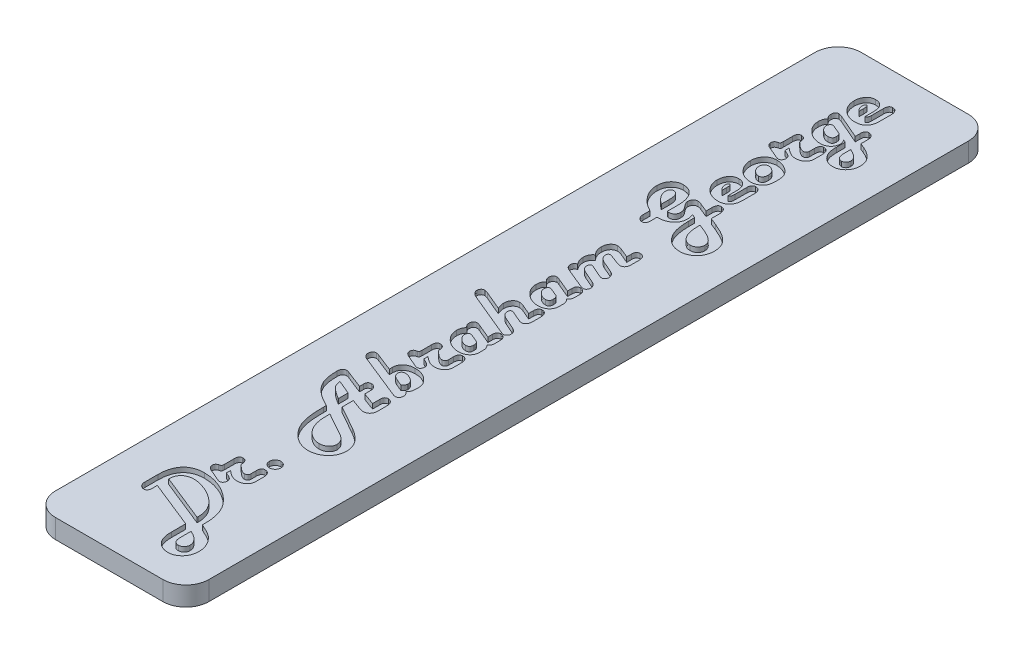
SolidWorks part; units mm, degrees
ref_plane "Front Plane" through (0, 0, 0) normal (0, 0, 1) x (1, 0, 0)
ref_plane "Top Plane" through (0, 0, 0) normal (0, 1, 0) x (1, 0, 0)
ref_plane "Right Plane" through (0, 0, 0) normal (1, 0, 0) x (0, 0, -1)
sketch "Sketch1" plane through (0, 0, 0) normal (0, 0, 1) x (1, 0, 0)
  line L0 (0, 1.5875) -> (0, -1.5875)
  line L1 (-12.7, 0) -> (12.7, 0) construction
  point P6 (0, 0)
  dimension "Width" = 25.4
  dimension "Thk" = 3.175
sketch "Sketch2" plane through (0, 0, 0) normal (1, 0, 0) x (0, 0, -1)
  line L0 (66.675, 0) -> (-66.675, 0)
  point P4 (0, 0)
  dimension "Length" = 133.35
sketch "Sketch3" plane through (0, 0, 0) normal (0, 0, 1) x (1, 0, 0)
  line L1 (12.7, 1.5875) -> (-12.7, 1.5875)
  line L2 (12.7, 1.5875) -> (12.7, -1.5875)
  line L3 (12.7, -1.5875) -> (-12.7, -1.5875)
  line L4 (-12.7, 1.5875) -> (-12.7, -1.5875)
  line L5 (12.7, 1.5875) -> (-12.7, -1.5875) construction
  line L6 (12.7, -1.5875) -> (-12.7, 1.5875) construction
  point P0 (0, 0)
extrude "Boss-Extrude1" add sketch "Sketch3" along normal up to vertex (66.675 mm away) and the other way up to vertex (66.675 mm away) up to point (0, 0, 66.675) other way up to point (0, 0, -66.675)
sketch "Sketch5" plane through (0, 1.5875, 0) normal (0, 1, 0) x (1, 0, 0)
  line L2 (9.652, -66.675) -> (-9.398, -66.675) construction
  line L3 (-12.7, -63.5025) -> (-12.7, 63.627) construction
  line L12 (12.7, -66.675) -> (12.7, 66.675)
  line L13 (12.7, 66.675) -> (-12.7, 66.675)
  line L14 (-12.7, 66.675) -> (-12.7, -66.675)
  line L15 (-12.7, -66.675) -> (12.7, -66.675)
  line L16 (12.7, -62.865) -> (12.7, 62.865)
  line L17 (8.89, 66.675) -> (-8.89, 66.675)
  line L18 (-12.7, 62.865) -> (-12.7, -62.865)
  line L19 (-8.89, -66.675) -> (8.89, -66.675)
  arc A8 (12.7, 62.865) -> (8.89, 66.675) centre (8.89, 62.865) ccw
  arc A9 (-8.89, 66.675) -> (-12.7, 62.865) centre (-8.89, 62.865) ccw
  arc A10 (12.7, -62.865) -> (8.89, -66.675) centre (8.89, -62.865) cw
  arc A11 (-8.89, -66.675) -> (-12.7, -62.865) centre (-8.89, -62.865) cw
  dimension "D2" = 3.81
  dimension "D1" = 0
extrude "Cut-Extrude2" cut sketch "Sketch5" against normal through all flip side to cut
sketch "Sketch4" plane through (0, 1.5875, 0) normal (0, 1, 0) x (1, 0, 0)
  line L0 (0, 0) -> (2.54, 0) construction
  line L1 (2.54, -66.675) -> (2.54, 66.675) construction
  line L2 (8.89, 66.675) -> (-8.89, 66.675) construction
  text T0 "Dr. Abraham George" font "Harlow Solid Italic" height in points 36
  point P8 (2.54, 0)
  dimension "D1" = 2.54
extrude "Cut-Extrude1" cut sketch "Sketch4" against normal blind 0.7937
